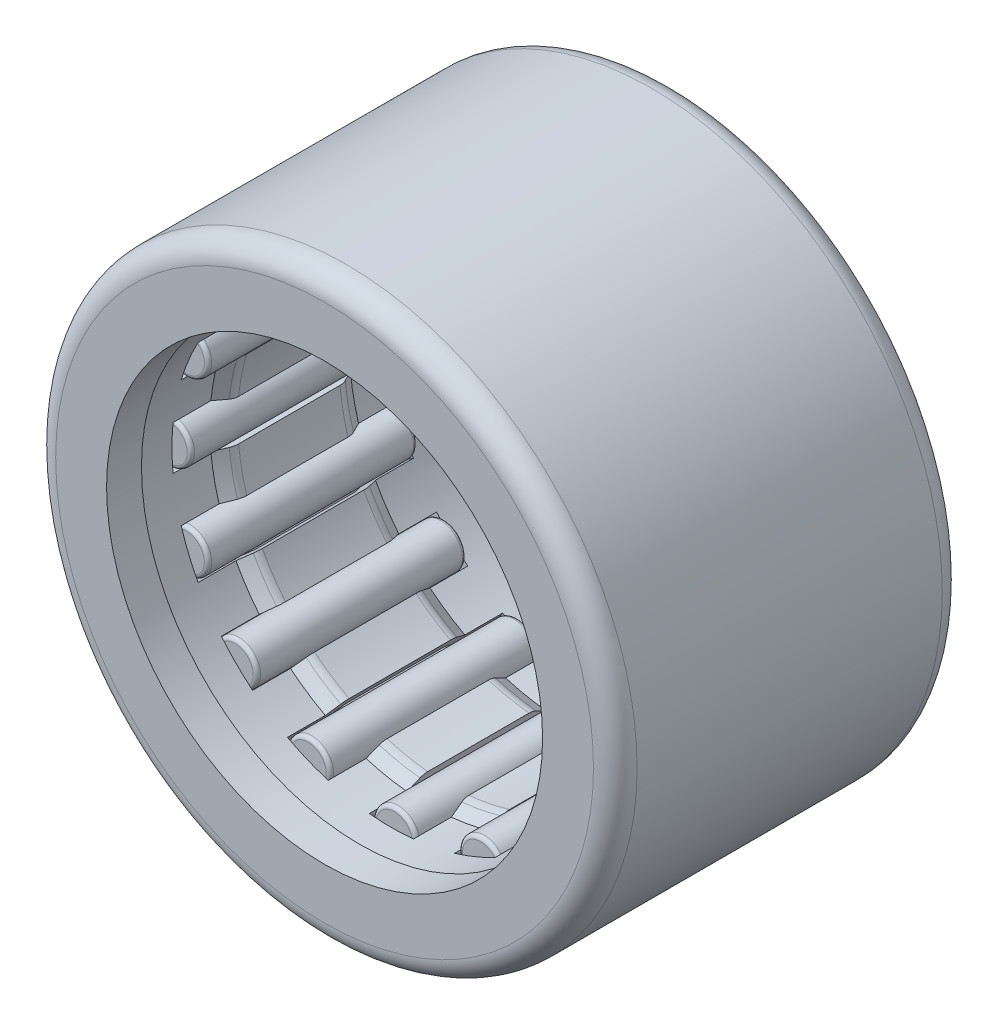
SolidWorks part; units mm, degrees
ref_plane "Front Plane" through (0, 0, 0) normal (0, 0, 1) x (1, 0, 0)
ref_plane "Top Plane" through (0, 0, 0) normal (0, 1, 0) x (1, 0, 0)
ref_plane "Right Plane" through (0, 0, 0) normal (1, 0, 0) x (0, 0, -1)
sketch "Sketch1" plane through (0, 0, 0) normal (0, 0, 1) x (1, 0, 0)
  circle A0 centre (0, 0) radius 7
  circle A1 centre (0, 0) radius 10
  dimension "OD" = 20
  dimension "ID" = 14
sketch "Sketch2" plane through (0, 0, 0) normal (1, 0, 0) x (0, 0, -1)
  line L0 (-6, 0) -> (6, 0) construction
  line L2 (-6, -7) -> (-6, 7) construction
  line L3 (6, 10) -> (-6, 10) construction
  line L11 (0, 0) -> (0, 10) construction
  line L16 (6, -10) -> (6, 10) construction
  line L17 (-6, 7) -> (6, 7) construction
  line L18 (-6, -7) -> (6, -7) construction
  point P4 (0, 0)
  point P8 (0, 10)
  point P10 (-6, 0)
  dimension "For Shaft Diameter" = 14
  dimension "Width" = 12
  dimension "For Housing ID" = 20
sketch "Sketch3" plane through (0, 0, 0) normal (1, 0, 0) x (0, 0, -1)
  line L0 (-6, -7) -> (-6, 7) construction
  line L2 (0, 10) -> (0, 9) construction
  line L3 (0, 9) -> (0, 8) construction
  line L4 (0, 8) -> (0, 7) construction
  line L16 (4.8, 9) -> (4.8, 7.5)
  line L17 (4.8, 7.5) -> (6, 7.5)
  line L18 (6, 7.5) -> (6, 10)
  line L19 (6, 10) -> (-6, 10)
  line L20 (-6, 10) -> (-6, 7.5)
  line L21 (-6, 7.5) -> (-4.8, 7.5)
  line L22 (-4.8, 7.5) -> (-4.8, 9)
  line L23 (-4.8, 9) -> (4.8, 9)
  point P17 (0, 7.5)
  dimension "D1" = 9.6
revolve "Revolve1" add sketch "Sketch3" angle 360 about L0
fillet "Fillet1" radius 0.75 2 edges at (10, 0, -6) (10, 0, 6)
sketch "Sketch4" plane through (0, 0, 0) normal (1, 0, 0) x (0, 0, -1)
  line L0 (0, 8.5) -> (0, 7.75) construction
  line L2 (-6, 7.5) -> (-4.8, 7.5) construction
  line L3 (-3.6, 7) -> (3.6, 7)
  line L4 (-3.6, 7) -> (-3.6, 7.75)
  line L5 (-3.6, 7.75) -> (3.6, 7.75)
  line L6 (3.6, 7) -> (3.6, 7.75)
  line L7 (0, 9) -> (0, 8) construction
  line L8 (-3.6, 7.375) -> (3.6, 7.375) construction
  line L9 (-4.8, 7.5) -> (-3.6, 7.5) construction
  point P15 (3.7016, 7.5)
  point P16 (-3.7016, 7.5)
  dimension "D1" = 0.1016
revolve "Revolve2" add sketch "Sketch4" angle 360 about L5
fillet "Fillet2" radius 0.127 2 edges at (0, 7, 3.6) (0, 7, -3.6)
sketch "Sketch5" plane through (0, 0, 0) normal (0, 0, 1) x (1, 0, 0)
  line L0 (0, 0) -> (0.75, 7.75) construction
  line L1 (0, -7) -> (0, 7) construction
  line L2 (0.75, 7.75) -> (-0.75, 7.75) construction
  line L3 (-0.75, 7.75) -> (0, 0) construction
  circle A0 centre (0, 7.75) radius 0.75
  circle A1 centre (0, 7.75) radius 0.75
  dimension "D1" = 11.055
pattern_circular "CirPattern1" count 16 over 360 about axis through (0, 0, 0) along (0, 0, 1) of bodies 105
sketch "Sketch6" plane through (0, 0, 0) normal (1, 0, 0) x (0, 0, -1)
  line L0 (0, 7.5) -> (0, 8) construction
  line L1 (-4.8, 7.5508) -> (4.8, 7.5508) construction
  line L2 (-4.8, 7.5508) -> (-4.8, 8.25)
  line L3 (-4.8, 8.25) -> (-2.9164, 8.25) construction
  line L5 (-4.8, 7.5508) -> (-2.4, 7.5508)
  line L6 (-2.4, 7.5508) -> (-1.879, 7.25)
  line L7 (-1.879, 7.25) -> (1.879, 7.25)
  line L8 (4.8, 9) -> (4.8, 7.5) construction
  line L9 (-4.8, 7.5) -> (-4.8, 9) construction
  line L10 (-6, 7.5) -> (-4.8, 7.5) construction
  line L13 (0, 7) -> (0, 7.5) construction
  line L14 (0, 8) -> (0, 7) construction
  line L15 (2.4, 7.5508) -> (1.879, 7.25)
  line L16 (-4.8, 8.25) -> (-2.9164, 8.25)
  line L17 (-2.9164, 8.25) -> (-1.7053, 7.5508)
  line L18 (-1.7053, 7.5508) -> (1.7053, 7.5508)
  line L21 (-1.879, 7.25) -> (-1.7053, 7.5508) construction
  line L22 (4.8, 7.5508) -> (2.4, 7.5508)
  line L23 (4.8, 7.5508) -> (4.8, 8.25)
  line L24 (4.8, 8.25) -> (2.9164, 8.25)
  line L25 (2.9164, 8.25) -> (1.7053, 7.5508)
  line L26 (0, 7) -> (-1.2, 7) construction
  line L29 (-3.6, 7) -> (3.6, 7) construction
  line L30 (-1.2, 7) -> (-2.4, 7) construction
  line L31 (-2.4, 7) -> (-3.6, 7) construction
  point P10 (0, 7.25)
  point P18 (0, 7.5)
  point P24 (0, 7.25)
  point P28 (0, 7.5508)
  dimension "D1" = 0.0508
  dimension "D2" = 30
revolve "Revolve3" add sketch "Sketch6" angle 360 about L0
fillet "Fillet3" radius 0.508 2 edges at (7.25, 0, 1.879) (7.25, 0, -1.879)
sketch "Sketch7" plane through (0, 0, 0) normal (0, 0, 1) x (1, 0, 0)
  line L0 (0, 7) -> (0, 7.75) construction
  line L1 (0, 7) -> (0, 7.75) construction
  line L3 (-0.6596, 6.9492) -> (0.6596, 6.9492)
  line L4 (-0.6596, 6.9492) -> (-0.942, 8.5508)
  line L5 (-0.942, 8.5508) -> (0.942, 8.5508)
  line L6 (0.6596, 6.9492) -> (0.942, 8.5508)
  line L7 (0, 8.5508) -> (0, 6.9492) construction
  line L8 (-0.8008, 7.75) -> (0.8008, 7.75) construction
  circle A0 centre (0, 7.75) radius 0.75 construction
  circle A1 centre (0, 7.75) radius 0.8008 construction
  dimension "D2" = 20
  dimension "D1" = 0.0508
extrude "Cut-Extrude1" cut sketch "Sketch7" along normal up to vertex (3.7016 mm away) and the other way up to vertex (3.7016 mm away) up to point (0, 7.5, 3.7016) other way up to point (0, 7.5, -3.7016)
pattern_circular "CirPattern2" count 16 over 360 about axis through (0, 0, 0) along (0, 0, 1) of "Cut-Extrude1"
equation "\"D1@Fillet1\" =  ( \"OD@Sketch1\" - \"For Shaft Diameter@Sketch2\" )  * .125"
equation "\"D1@CirPattern1\" = 360 / \"D1@Sketch5\" / 2"
equation "\"D2\"= \"D1\""
equation "\"D1@CirPattern2\" = \"D1@CirPattern1\""
equation "\"D1@Sketch3\" = \"Width@Sketch2\" * .8"
